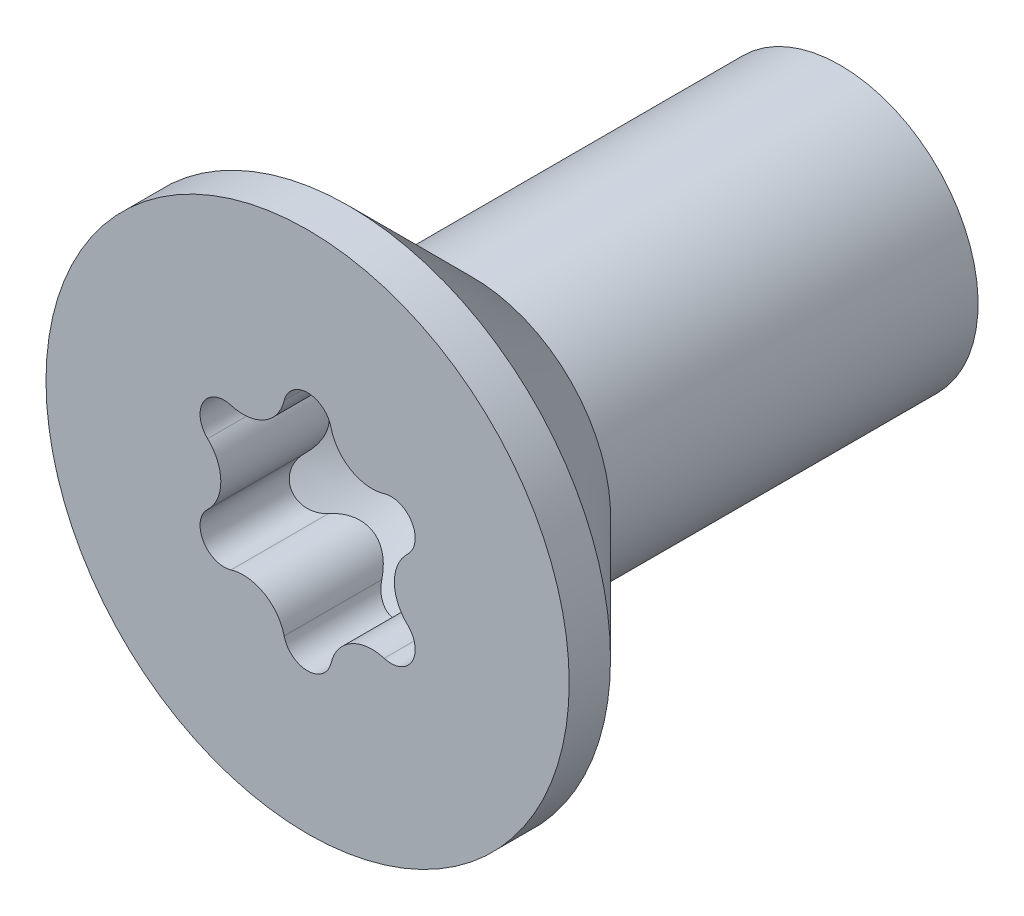
SolidWorks part; units mm, degrees
ref_plane "Front Plane" through (0, 0, 0) normal (0, 0, 1) x (1, 0, 0)
ref_plane "Top Plane" through (0, 0, 0) normal (0, 1, 0) x (1, 0, 0)
ref_plane "Right Plane" through (0, 0, 0) normal (1, 0, 0) x (0, 0, -1)
other "Configuration Table"
sketch "BodySke" plane through (0, 0, 0) normal (1, 0, 0) x (0, 0, -1)
  line L0 (0, 0) -> (-1787.2758, 0) construction
  line L1 (0, 0) -> (0, 1.9)
  line L2 (0.3, 1.9) -> (1.2, 1)
  line L3 (0.3, -1.9) -> (1.2, -1) construction
  line L4 (1.2, 1) -> (4, 1)
  line L5 (4, 1) -> (4, 0)
  line L6 (4, 0) -> (0, 0)
  line L7 (0, 0) -> (0, 50000) construction
  line L8 (0.3, 1.9) -> (0, 1.9)
  dimension "D" = 2
  dimension "Dk" = 3.8
  dimension "K" = 1.2
  dimension "L" = 4
  dimension "D1" = 90
  dimension "B" = 4
revolve "Base-Revolve" add sketch "BodySke" angle 360 about L0
cosmetic thread "ThreadCosmetic" [suppressed] parameters "ThdLen"=2.8, "MinorDia"=1.548
sketch "PreBSke" plane through (0, 0, 0) normal (1, 0, 0) x (0, 0, -1)
  line L0 (0, 0) -> (-50000, 0) construction
  line L1 (0, 0) -> (0, 0.875)
  line L2 (0, 2.2) -> (0, -2.2) construction
  line L3 (0, 0.875) -> (0.64, 0.875)
  line L4 (0.64, 0.875) -> (1.1658, 0)
  line L5 (1.1658, 0) -> (0, 0)
  line L6 (0.64, -0.875) -> (1.1658, 0) construction
  dimension "T" = 0.64
  dimension "A" = 1.75
  dimension "D1" = 118
revolve "PreBroach" cut sketch "PreBSke" angle 360 about L0
sketch "HexSke" plane through (0, 0, 0) normal (0, 0, 1) x (1, 0, 0)
  line L0 (0, 0) -> (-43301.2702, 25000) construction
  line L1 (0, 0) -> (-43301.2702, -25000) construction
  line L2 (0, 0) -> (50000, 0) construction
  arc A0 (-0.7263, -0.2227) -> (-0.7263, 0.2227) centre (-0.9365, 0) ccw
  arc A1 (-0.7578, 0.4375) -> (-0.7263, 0.2227) centre (-0.6062, 0.35) ccw
  arc A2 (-0.7263, -0.2227) -> (-0.7578, -0.4375) centre (-0.6062, -0.35) ccw
  arc A3 (-0.5561, 0.5177) -> (-0.7578, 0.4375) centre (-0.6062, 0.35) ccw
  circle A4 centre (0, 0) radius 0.6303 construction
  circle A5 centre (0, 0) radius 0.875 construction
  arc A6 (-0.5561, 0.5177) -> (-0.1703, 0.7404) centre (-0.4683, 0.8111) ccw
  arc A7 (0, 0.875) -> (-0.1703, 0.7404) centre (0, 0.7) ccw
  arc A8 (0.1703, 0.7404) -> (0, 0.875) centre (0, 0.7) ccw
  arc A9 (0.1703, 0.7404) -> (0.5561, 0.5177) centre (0.4683, 0.8111) ccw
  arc A10 (0.7578, 0.4375) -> (0.5561, 0.5177) centre (0.6062, 0.35) ccw
  arc A11 (0.7263, 0.2227) -> (0.7578, 0.4375) centre (0.6062, 0.35) ccw
  arc A12 (0.7263, 0.2227) -> (0.7263, -0.2227) centre (0.9365, 0) ccw
  arc A13 (0.7578, -0.4375) -> (0.7263, -0.2227) centre (0.6062, -0.35) ccw
  arc A14 (0.5561, -0.5177) -> (0.7578, -0.4375) centre (0.6062, -0.35) ccw
  arc A15 (0.5561, -0.5177) -> (0.1703, -0.7404) centre (0.4683, -0.8111) ccw
  arc A16 (0, -0.875) -> (0.1703, -0.7404) centre (0, -0.7) ccw
  arc A17 (-0.1703, -0.7404) -> (0, -0.875) centre (0, -0.7) ccw
  arc A18 (-0.1703, -0.7404) -> (-0.5561, -0.5177) centre (-0.4683, -0.8111) ccw
  arc A19 (-0.7578, -0.4375) -> (-0.5561, -0.5177) centre (-0.6062, -0.35) ccw
  circle A20 centre (0, 0) radius 0.875 construction
  circle A21 centre (0, 0) radius 0.875
  point P56 (0, 0)
  circle M6 centre (0, 0) radius 0.875
  dimension "B" = 1.2605
  dimension "Ri" = 0.175
  dimension "Re" = 0.3062
  dimension "D1" = 60
  dimension "D5" = 6
extrude "Hexalobular" add sketch "HexSke" against normal up to next contours A2 A0 A1 M6 | A7 A3 A6 M6 | A10 A8 A9 M6 | A13 A11 A12 M6 | A16 A14 A15 M6 | A19 A17 A18 M6
sketch "ThdSchSke" plane through (0, 0, 0) normal (1, 0, 0) x (0, 0, -1)
  line L0 (4.1305, 1) -> (4, 0.774)
  line L1 (4, 0.774) -> (3.8695, 1)
  line L2 (3.8695, 1) -> (4.1305, 1)
  line L3 (4, 0.774) -> (4, 1) construction
  line L4 (4, -1) -> (4, 1) construction
  line L5 (4, 1) -> (1.2, 1) construction
  line L6 (0, 0) -> (-50000, 0) construction
  dimension "MinorDia" = 1.548
  dimension "D1" = 60
  dimension "D2" = 0.261
revolve "ThreadSchematic" cut sketch "ThdSchSke" angle 360 about L6
ref_plane "ThreadPlane" through (0, 0, -1.2) normal (0, 0, -1) x (-1, 0, 0)
pattern_linear "ThdSchPat" [suppressed] count 11
equation "\"MinorDia@ThreadCosmetic\" = \"MinorDia@ThdSchSke\""
equation "\"ThdLen@ThreadCosmetic\" = \"ThreadLength\""
equation "\"Ri@HexSke\"= .1 * \"A@PreBSke\""
equation "\"Re@HexSke\"= .175 * \"A@PreBSke\""
equation "\"ThreadLength\"= IIF ( \"B@BodySke\" = \"L@BodySke\" , \"L@BodySke\" - \"K@BodySke\" , \"B@BodySke\" )"
equation "\"ThdLen@ThreadPlane\"=\"ThreadLength\""
